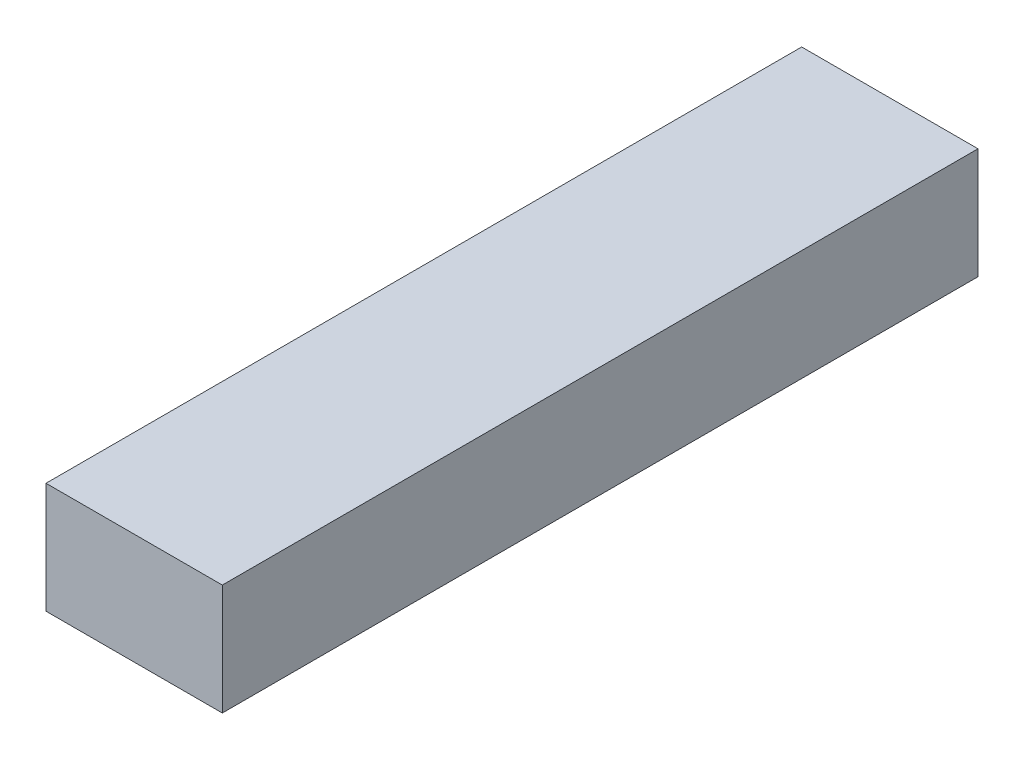
SolidWorks part; units mm, degrees
ref_plane "Front Plane" through (0, 0, 0) normal (0, 0, 1) x (1, 0, 0)
ref_plane "Top Plane" through (0, 0, 0) normal (0, 1, 0) x (1, 0, 0)
ref_plane "Right Plane" through (0, 0, 0) normal (1, 0, 0) x (0, 0, -1)
sketch "Sketch1" plane through (0, 0, 0) normal (0, 0, 1) x (1, 0, 0)
  line L7 (-35, -22) -> (35, -22)
  line L8 (-35, -22) -> (-35, 22)
  line L9 (-35, 22) -> (35, 22)
  line L10 (35, -22) -> (35, 22)
  line L11 (-35, -22) -> (35, 22) construction
  line L12 (-35, 22) -> (35, -22) construction
  point P10 (0, 0)
  dimension "D1" = 70
  dimension "D2" = 44
extrude "Boss-Extrude1" add sketch "Sketch1" along normal blind 300
